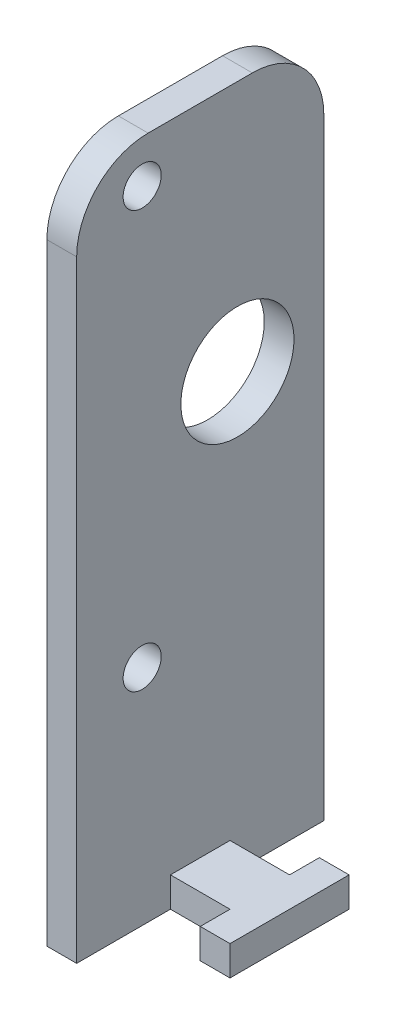
SolidWorks part; units mm, degrees
ref_plane "Front Plane" through (0, 0, 0) normal (0, 0, 1) x (1, 0, 0)
ref_plane "Top Plane" through (0, 0, 0) normal (0, 1, 0) x (1, 0, 0)
ref_plane "Right Plane" through (0, 0, 0) normal (1, 0, 0) x (0, 0, -1)
sketch "Sketch1" plane through (0, 0, 0) normal (0, 1, 0) x (1, 0, 0)
  line L1 (40, -30) -> (-40, -30)
  line L2 (40, -30) -> (40, 30)
  line L3 (40, 30) -> (-40, 30)
  line L4 (-40, -30) -> (-40, 30)
  line L5 (40, -30) -> (-40, 30) construction
  line L6 (40, 30) -> (-40, -30) construction
  point P0 (0, 0)
  dimension "D1" = 80
  dimension "D2" = 60
extrude "Boss-Extrude1" add sketch "Sketch1" along normal blind 2.5 contours L2 L1 L4 L3
sketch "Sketch2" plane through (0, 0, 0) normal (0, 1, 0) x (1, 0, 0)
  line L0 (0, -30) -> (0, -24)
  line L1 (40, -30) -> (-40, -30) construction
  line L2 (-11, -24) -> (21, -24)
  line L3 (-8.625, -24) -> (0, -24)
  line L4 (-11, -24) -> (-6.25, -24)
  line L5 (21, -24) -> (16.25, -24)
  line L6 (16.25, -30) -> (-6.25, -30)
  line L7 (16.25, -30) -> (16.25, -18)
  line L8 (16.25, -18) -> (-6.25, -18)
  line L9 (-6.25, -30) -> (-6.25, -18)
  line L10 (16.25, -30) -> (-6.25, -18) construction
  line L11 (16.25, -18) -> (-6.25, -30) construction
  line L12 (-10.225, -24) -> (0, -24)
  line L13 (-8.625, -24) -> (0, -24)
  circle A2 centre (0, -24) radius 2.5
  circle A3 centre (-8.625, -24) radius 1.6
  circle A4 centre (18.625, -24) radius 1.6
  point P5 (0, -30)
  point P15 (5, -24)
  dimension "D5" = 3.2
  dimension "D7" = 3.2
  dimension "D8" = 5
  dimension "D1" = 6
  dimension "D2" = 11
  dimension "D3" = 32
  dimension "D4" = 4.75
  dimension "D6" = 4.75
  dimension "D9" = 12
  dimension "D10" = 22.5
extrude "Cut-Extrude4" cut sketch "Sketch2" against normal through all and the other way through all contours A2 L2 L7 L8 L9 | A2 L0 L6 L7 L2 | L0 A2 L2 | L2 A2 | L2 A2 L0 | A2 L2 L9 L6 L0 | A3 | A4
sketch "Sketch3" plane through (0, 2.5, 0) normal (0, 1, 0) x (1, 0, 0)
  line L0 (-10.225, -24) -> (0.275, -24)
  line L3 (-40, -30) -> (-37.5, -30)
  line L4 (-40, -30) -> (-40, -9.5)
  line L5 (-40, -9.5) -> (-37.5, -9.5)
  line L6 (-37.5, -30) -> (-37.5, -9.5)
  circle A0 centre (-8.625, -24) radius 1.6 construction
  line M13 (-40, 30) -> (-40, -30)
  line M14 (-40, -30) -> (-6.25, -30)
  dimension "D1" = 10.5
  dimension "D2" = 2.5
  dimension "D3" = 20.5
extrude "Boss-Extrude2" add sketch "Sketch3" along normal blind 66.5 contours L6 L5 M14 M13
sketch "Sketch4" plane through (0, 2.5, 0) normal (0, 1, 0) x (1, 0, 0)
  line L1 (40, -30) -> (-40, -30)
  line L2 (40, -30) -> (40, -35.5)
  line L3 (40, -35.5) -> (-40, -35.5)
  line L4 (-40, -30) -> (-40, -35.5)
  dimension "D1" = 5.5
extrude "Boss-Extrude3" add sketch "Sketch4" against normal up to surface (2.5 mm away) up to face at (18.625, 0, 22.4)
sketch "Sketch5" plane through (0, 2.5, 0) normal (0, 1, 0) x (1, 0, 0)
  line L1 (-37.5, -30) -> (-40, -30)
  line L2 (-37.5, -30) -> (-37.5, -35.5)
  line L3 (-37.5, -35.5) -> (-40, -35.5)
  line L4 (-40, -30) -> (-40, -35.5)
extrude "Boss-Extrude4" add sketch "Sketch5" along normal up to surface (66.5 mm away) up to face at (-38.75, 69, 19.75)
sketch "Sketch6" plane through (0, 69, 0) normal (0, 1, 0) x (1, 0, 0)
  line L0 (-37.5, -35.5) -> (-37.5, -9.5) construction
  line L1 (-40, -9.5) -> (-37.5, -9.5)
  line L2 (-40, -9.5) -> (-40, -15)
  line L3 (-40, -15) -> (-37.5, -15)
  line L4 (-37.5, -9.5) -> (-37.5, -15)
  dimension "D1" = 5.5
extrude "Cut-Extrude5" cut sketch "Sketch6" against normal up to surface (66.5 mm away) up to face at (5, 2.5, 24)
sketch "Sketch7" plane through (0, 2.5, 0) normal (0, 1, 0) x (1, 0, 0)
  line L0 (-10.225, -24) -> (0.275, -24)
  line L1 (15.525, -24) -> (-14.975, -24)
  line L2 (15.525, -24) -> (18.625, -24)
  line L3 (-14.975, -24) -> (-24.175, -24)
  circle A0 centre (-8.625, -24) radius 1.6 construction
  point P8 (0.275, -24)
  dimension "D4" = 9.2
  dimension "D1" = 10.5
  dimension "D2" = 30.5
  dimension "D3" = 3.1
sketch "Sketch9" plane through (0, 2.5, 0) normal (0, 1, 0) x (1, 0, 0)
  line L0 (-10.225, -24) -> (-37.5, -24)
  line L1 (-37.5, -35.5) -> (-37.5, -15) construction
  line L2 (-37.5, -24) -> (-37.5, -35.5)
  line L3 (-37.5, -24) -> (-37.5, -12.5)
  line L4 (-37.5, -12.5) -> (-40, -12.5)
  line L5 (-40, -15) -> (-40, 30) construction
  line L6 (-40, -12.5) -> (-40, -15)
  line L7 (-40, -15) -> (-37.5, -15) construction
  line L8 (-40, -15) -> (-37.5, -15)
  line L9 (-37.5, -15) -> (-37.5, -12.5)
  dimension "D1" = 11.5
extrude "Boss-Extrude5" add sketch "Sketch9" along normal up to surface (66.5 mm away) contours L4 L6 L8 L9 up to face at (-38.75, 69, 25.25)
sketch "Sketch11" plane through (-37.5, 0, 0) normal (1, 0, 0) x (0, 0, -1)
  line L0 (-24, 69) -> (-24, 54)
  line L1 (-35.5, 69) -> (-12.5, 69) construction
  circle A0 centre (-24, 54) radius 4.75
  dimension "D2" = 9.5
  dimension "D1" = 15
extrude "Cut-Extrude6" cut sketch "Sketch11" against normal up to surface (2.5 mm away) contours A0 up to face at (-40, 23.8333, 6)
sketch "Sketch13" plane through (-40, 0, 0) normal (-1, 0, 0) x (0, 0, 1)
  line L0 (24, 54) -> (32, 54)
  line L1 (32, 36.5) -> (32, 71.5)
  point P7 (32, 54)
  dimension "D1" = 8
  dimension "D2" = 35
sketch "Sketch15" plane through (0, 69, 0) normal (0, 1, 0) x (1, 0, 0)
  line L1 (-40, -12.5) -> (-37.5, -12.5)
  line L2 (-40, -12.5) -> (-40, -35.5)
  line L3 (-40, -35.5) -> (-37.5, -35.5)
  line L4 (-37.5, -12.5) -> (-37.5, -35.5)
extrude "Boss-Extrude6" add sketch "Sketch15" along normal blind 8
sketch "Sketch17" plane through (0, 0, 35.5) normal (0, 0, 1) x (1, 0, 0)
  line L1 (-40, 77) -> (-37.5, 77)
  line L2 (-40, 77) -> (-40, 2.5)
  line L3 (-40, 2.5) -> (-37.5, 2.5)
  line L4 (-37.5, 77) -> (-37.5, 2.5)
extrude "Boss-Extrude7" add sketch "Sketch17" along normal blind 2
sketch "Sketch18" plane through (-40, 0, 0) normal (-1, 0, 0) x (0, 0, 1)
  circle A0 centre (32, 36.5) radius 1.6
  circle A1 centre (32, 71.5) radius 1.6
  dimension "D1" = 3.2
  dimension "D2" = 3.2
extrude "Cut-Extrude7" cut sketch "Sketch18" against normal up to surface (2.5 mm away) up to face at (-37.5, 54, 19.25)
sketch "Sketch21" plane through (0, 0, 35.5) normal (0, 0, 1) x (1, 0, 0)
  line L1 (-40, 2.5) -> (40, 2.5)
  line L2 (-40, 2.5) -> (-40, 0)
  line L3 (-40, 0) -> (40, 0)
  line L4 (40, 2.5) -> (40, 0)
extrude "Boss-Extrude8" add sketch "Sketch21" along normal up to surface (2 mm away) up to face at (-38.75, 39.75, 37.5)
sketch "Sketch22" plane through (-37.5, 0, 0) normal (1, 0, 0) x (0, 0, -1)
  line L0 (-37.5, 2.5) -> (-12.5, 2.5) construction
  line L1 (-12.5, 77) -> (-16.75, 77)
  line L2 (-12.5, 77) -> (-12.5, 2.5)
  line L3 (-12.5, 2.5) -> (-16.75, 2.5)
  line L4 (-16.75, 77) -> (-16.75, 2.5)
  dimension "D1" = 4.25
extrude "Cut-Extrude8" cut sketch "Sketch22" against normal up to surface (2.5 mm away) up to face at (-40, 36.5, 33.6)
fillet "Fillet1" radius 5 2 edges at (-38.75, 77, 37.5) (-38.75, 77, 16.75)
sketch "Sketch23" plane through (0, 2.5, 0) normal (0, 1, 0) x (1, 0, 0)
  line L0 (20.225, -24) -> (55.225, -24)
  line L1 (40, 30) -> (40, -37.5)
  line L6 (40, -37.5) -> (55.225, -37.5)
  line L7 (55.225, -37.5) -> (55.225, 30)
  line L8 (55.225, 30) -> (40, 30)
  circle A0 centre (18.625, -24) radius 1.6 construction
  dimension "D1" = 35
extrude "Boss-Extrude10" add sketch "Sketch23" against normal up to surface (2.5 mm away) contours L8 L1 L6 L7 up to face at (0, 0, 3.75)
sketch "Sketch24" plane through (0, 2.5, 0) normal (0, 1, 0) x (1, 0, 0)
  line L0 (55.225, -37.5) -> (55.225, 30) construction
  line L1 (-40, 30) -> (55.225, 30)
  line L2 (-40, 30) -> (-40, 20)
  line L3 (-40, 20) -> (55.225, 20)
  line L4 (55.225, 30) -> (55.225, 20)
  dimension "D1" = 10
extrude "Cut-Extrude9" cut sketch "Sketch24" against normal through all
sketch "Sketch26" plane through (0, 2.5, 0) normal (0, 1, 0) x (1, 0, 0)
  line L0 (-24.175, -37.5) -> (-24.175, -16.75)
  line L1 (55.225, -37.5) -> (-37.5, -37.5) construction
  line L2 (-24.175, -16.75) -> (-26.675, -16.75)
  line L3 (-26.675, -16.75) -> (-26.675, -37.5)
  line L4 (-26.675, -37.5) -> (-24.175, -37.5)
extrude "Boss-Extrude11" add sketch "Sketch26" along normal up to surface (74.5 mm away) up to face at (-38.75, 77, 27.125)
sketch "Sketch27" plane through (-24.175, 0, 0) normal (1, 0, 0) x (0, 0, -1)
  line L0 (-24, 2.5) -> (-24, 36.275)
  line L2 (-24, 36.275) -> (-32, 36.275)
  line L4 (-32, 18.775) -> (-32, 53.775)
  circle A0 centre (-24, 36.275) radius 4.75
  circle A1 centre (-32, 53.775) radius 1.6
  circle A2 centre (-32, 18.775) radius 1.6
  point P4 (-32, 36.275)
  dimension "D2" = 9.5
  dimension "D5" = 3.2
  dimension "D6" = 3.2
  dimension "D1" = 33.775
  dimension "D3" = 8
  dimension "D4" = 35
extrude "Cut-Extrude10" cut sketch "Sketch27" against normal up to surface (2.5 mm away) contours L0 A0 L2 | L2 A0 L0 | A2 | A1 up to face at (-26.675, 39.75, 27.125)
sketch "Sketch28" plane through (0, 77, 0) normal (0, 1, 0) x (1, 0, 0)
  line L1 (-40, -16.75) -> (-37.5, -16.75)
  line L2 (-40, -16.75) -> (-40, -37.5)
  line L3 (-40, -37.5) -> (-37.5, -37.5)
  line L4 (-37.5, -16.75) -> (-37.5, -37.5)
extrude "Cut-Extrude11" cut sketch "Sketch28" against normal up to surface (74.5 mm away) up to face at (5, 2.5, 24)
sketch "Sketch29" plane through (-24.175, 0, 0) normal (1, 0, 0) x (0, 0, -1)
  line L0 (-32, 55.375) -> (-32, 57.375)
  line L1 (-32, 36.5) -> (-32, 71.5) construction
  line L2 (-16.75, 77) -> (-16.75, 2.5) construction
  line L3 (-37.5, 77) -> (-16.75, 77)
  line L4 (-37.5, 77) -> (-37.5, 57.375)
  line L5 (-37.5, 57.375) -> (-16.75, 57.375)
  line L6 (-16.75, 77) -> (-16.75, 57.375)
  circle A0 centre (-32, 53.775) radius 1.6 construction
  dimension "D1" = 2
extrude "Cut-Extrude12" cut sketch "Sketch29" against normal up to surface (2.5 mm away) contours L4 L3 L6 L5 up to face at (-26.675, 36.275, 19.25)
fillet "Fillet2" radius 6 2 edges at (-25.425, 57.375, 16.75) (-25.425, 57.375, 37.5)
sketch "Sketch31" plane through (0, 2.5, 0) normal (0, 1, 0) x (1, 0, 0)
  line L1 (-40, 20) -> (-26.675, 20)
  line L2 (-40, 20) -> (-40, -37.5)
  line L3 (-40, -37.5) -> (-26.675, -37.5)
  line L4 (-26.675, 20) -> (-26.675, -37.5)
extrude "Cut-Extrude13" cut sketch "Sketch31" against normal up to surface (2.5 mm away) up to face at (7.6125, 0, 8.75)
sketch "Sketch33" plane through (0, 2.5, 0) normal (0, 1, 0) x (1, 0, 0)
  line L0 (55.225, -37.5) -> (-24.175, -37.5) construction
  line L1 (55.225, 20) -> (52.225, 20)
  line L2 (55.225, 20) -> (55.225, -37.5)
  line L3 (55.225, -37.5) -> (52.225, -37.5)
  line L4 (52.225, 20) -> (52.225, -37.5)
  dimension "D1" = 3
extrude "Cut-Extrude14" cut sketch "Sketch33" against normal up to surface (2.5 mm away) up to face at (14.275, 0, 8.75)
sketch "Sketch34" plane through (0, 2.5, 0) normal (0, 1, 0) x (1, 0, 0)
  line L0 (-24.175, -27.125) -> (-24.175, -24.625)
  line L1 (-24.175, -37.5) -> (-24.175, -16.75) construction
  line L2 (-24.175, -27.125) -> (-24.175, -29.625)
  line L3 (-24.175, -24.625) -> (-19.175, -24.625)
  line L4 (-24.175, -29.625) -> (-19.175, -29.625)
  line L5 (-19.175, -29.625) -> (-19.175, -32.125)
  line L6 (-19.175, -24.625) -> (-19.175, -22.125)
  line L7 (-19.175, -22.125) -> (-16.675, -22.125)
  line L8 (-16.675, -22.125) -> (-16.675, -32.125)
  line L9 (-16.675, -32.125) -> (-19.175, -32.125)
  line L10 (-24.175, -29.625) -> (-24.175, -37.5)
  line L11 (-24.175, -37.5) -> (52.225, -37.5)
  line L12 (52.225, -37.5) -> (52.225, 20)
  line L13 (52.225, 20) -> (-26.675, 20)
  line L14 (-26.675, 20) -> (-26.675, -16.75)
  line L15 (-26.675, -16.75) -> (-24.175, -16.75)
  line L16 (-24.175, -16.75) -> (-24.175, -24.625)
  dimension "D1" = 2.5
  dimension "D2" = 2.5
  dimension "D3" = 5
  dimension "D4" = 5
  dimension "D5" = 2.5
  dimension "D6" = 2.5
  dimension "D7" = 2.5
extrude "Cut-Extrude15" cut sketch "Sketch34" against normal up to surface (2.5 mm away)
